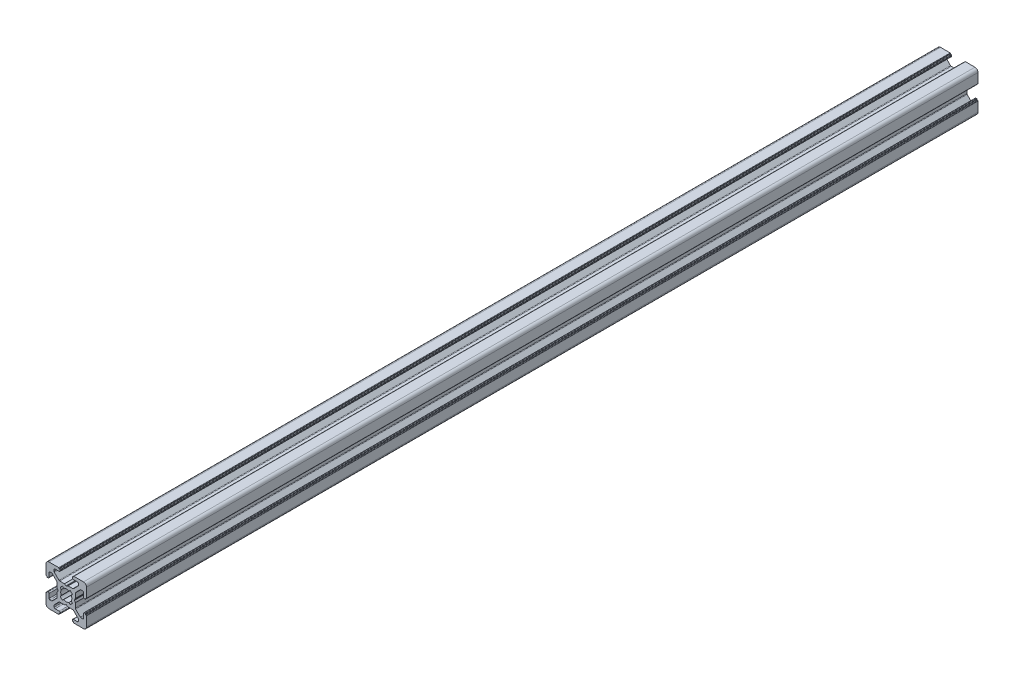
SolidWorks part; units mm, degrees
ref_plane "Ön Düzlem" through (0, 0, 0) normal (0, 0, 1) x (1, 0, 0)
ref_plane "Üst Düzlem" through (0, 0, 0) normal (0, 1, 0) x (1, 0, 0)
ref_plane "Sağ Düzlem" through (0, 0, 0) normal (1, 0, 0) x (0, 0, -1)
sketch "Çizim1" plane through (0, 0, 0) normal (0, 0, 1) x (1, 0, 0)
  line L0 (-2.9922, 1.9099) -> (-2.4453, 1.2582)
  line L1 (-2.4453, -1.2582) -> (-2.9922, -1.9099)
  line L2 (-1.9139, -2.9896) -> (-1.2582, -2.4453)
  line L3 (1.2582, -2.4453) -> (1.9139, -2.9896)
  line L4 (2.9922, -1.9099) -> (2.4453, -1.2582)
  line L5 (2.4453, 1.2582) -> (2.9922, 1.9099)
  line L6 (1.9139, 2.9896) -> (1.2582, 2.4453)
  line L7 (-1.2582, 2.4453) -> (-1.9139, 2.9896)
  line L8 (-3.75, 10) -> (-8.5, 10)
  line L9 (-3.55, 9.7) -> (-3.55, 9.8)
  line L10 (-3.2, 9.5) -> (-3.35, 9.5)
  line L11 (-3, 9) -> (-3, 9.3)
  line L12 (-5.5, 8.5) -> (-3.5, 8.5)
  line L13 (-6, 7.2678) -> (-6, 8)
  line L14 (-3.5858, 4.6464) -> (-5.8536, 6.9142)
  line L15 (-0.9536, 4.5) -> (-3.2322, 4.5)
  line L16 (-0.1, 4.0381) -> (-0.8536, 4.4732)
  line L17 (0.8536, 4.4732) -> (0.1, 4.0381)
  line L18 (3.2322, 4.5) -> (0.9536, 4.5)
  line L19 (5.8536, 6.9142) -> (3.5858, 4.6464)
  line L20 (6, 8) -> (6, 7.2678)
  line L21 (3.5, 8.5) -> (5.5, 8.5)
  line L22 (3, 9.3) -> (3, 9)
  line L23 (3.35, 9.5) -> (3.2, 9.5)
  line L24 (3.55, 9.8) -> (3.55, 9.7)
  line L25 (8.5, 10) -> (3.75, 10)
  line L26 (10, 3.75) -> (10, 8.5)
  line L27 (9.7, 3.55) -> (9.8, 3.55)
  line L28 (9.5, 3.2) -> (9.5, 3.35)
  line L29 (9, 3) -> (9.3, 3)
  line L30 (8.5, 5.5) -> (8.5, 3.5)
  line L31 (7.2678, 6) -> (8, 6)
  line L32 (4.6464, 3.5858) -> (6.9142, 5.8536)
  line L33 (4.5, 0.9536) -> (4.5, 3.2322)
  line L34 (4.0381, 0.1) -> (4.4732, 0.8536)
  line L35 (4.4732, -0.8536) -> (4.0381, -0.1)
  line L36 (4.5, -3.2322) -> (4.5, -0.9536)
  line L37 (6.9142, -5.8536) -> (4.6464, -3.5858)
  line L38 (8, -6) -> (7.2678, -6)
  line L39 (8.5, -3.5) -> (8.5, -5.5)
  line L40 (9.3, -3) -> (9, -3)
  line L41 (9.5, -3.35) -> (9.5, -3.2)
  line L42 (9.8, -3.55) -> (9.7, -3.55)
  line L43 (10, -8.5) -> (10, -3.75)
  line L44 (3.75, -10) -> (8.5, -10)
  line L45 (3.55, -9.7) -> (3.55, -9.8)
  line L46 (3.2, -9.5) -> (3.35, -9.5)
  line L47 (3, -9) -> (3, -9.3)
  line L48 (5.5, -8.5) -> (3.5, -8.5)
  line L49 (6, -7.2678) -> (6, -8)
  line L50 (3.5858, -4.6464) -> (5.8536, -6.9142)
  line L51 (0.9536, -4.5) -> (3.2322, -4.5)
  line L52 (0.1, -4.0381) -> (0.8536, -4.4732)
  line L53 (-0.8536, -4.4732) -> (-0.1, -4.0381)
  line L54 (-3.2322, -4.5) -> (-0.9536, -4.5)
  line L55 (-5.8536, -6.9142) -> (-3.5858, -4.6464)
  line L56 (-6, -8) -> (-6, -7.2678)
  line L57 (-3.5, -8.5) -> (-5.5, -8.5)
  line L58 (-3, -9.3) -> (-3, -9)
  line L59 (-3.35, -9.5) -> (-3.2, -9.5)
  line L60 (-3.55, -9.8) -> (-3.55, -9.7)
  line L61 (-8.5, -10) -> (-3.75, -10)
  line L62 (-10, -3.75) -> (-10, -8.5)
  line L63 (-9.7, -3.55) -> (-9.8, -3.55)
  line L64 (-9.5, -3.2) -> (-9.5, -3.35)
  line L65 (-9, -3) -> (-9.3, -3)
  line L66 (-8.5, -5.5) -> (-8.5, -3.5)
  line L67 (-7.2678, -6) -> (-8, -6)
  line L68 (-4.6464, -3.5858) -> (-6.9142, -5.8536)
  line L69 (-4.5, -0.9536) -> (-4.5, -3.2322)
  line L70 (-4.0381, -0.1) -> (-4.4732, -0.8536)
  line L71 (-4.4732, 0.8536) -> (-4.0381, 0.1)
  line L72 (-4.5, 3.2322) -> (-4.5, 0.9536)
  line L73 (-6.9142, 5.8536) -> (-4.6464, 3.5858)
  line L74 (-8, 6) -> (-7.2678, 6)
  line L75 (-8.5, 3.5) -> (-8.5, 5.5)
  line L76 (-9.3, 3) -> (-9, 3)
  line L77 (-9.5, 3.35) -> (-9.5, 3.2)
  line L78 (-9.8, 3.55) -> (-9.7, 3.55)
  line L79 (-10, 8.5) -> (-10, 3.75)
  arc A0 (-2.4453, 1.2582) -> (-2.4453, -1.2582) centre (0, 0) ccw
  arc A1 (-2.9922, -1.9099) -> (-1.9139, -2.9896) centre (0, 0) ccw
  arc A2 (-1.2582, -2.4453) -> (1.2582, -2.4453) centre (0, 0) ccw
  arc A3 (1.9139, -2.9896) -> (2.9922, -1.9099) centre (0, 0) ccw
  arc A4 (2.4453, -1.2582) -> (2.4453, 1.2582) centre (0, 0) ccw
  arc A5 (2.9922, 1.9099) -> (1.9139, 2.9896) centre (0, 0) ccw
  arc A6 (1.2582, 2.4453) -> (-1.2582, 2.4453) centre (0, 0) ccw
  arc A7 (-1.9139, 2.9896) -> (-2.9922, 1.9099) centre (0, 0) ccw
  arc A8 (-3.55, 9.8) -> (-3.75, 10) centre (-3.75, 9.8) ccw
  arc A9 (-3.55, 9.7) -> (-3.35, 9.5) centre (-3.35, 9.7) ccw
  arc A10 (-3, 9.3) -> (-3.2, 9.5) centre (-3.2, 9.3) ccw
  arc A11 (-3.5, 8.5) -> (-3, 9) centre (-3.5, 9) ccw
  arc A12 (-5.5, 8.5) -> (-6, 8) centre (-5.5, 8) ccw
  arc A13 (-6, 7.2678) -> (-5.8536, 6.9142) centre (-5.5, 7.2678) ccw
  arc A14 (-3.5858, 4.6464) -> (-3.2322, 4.5) centre (-3.2322, 5) ccw
  arc A15 (-0.8536, 4.4732) -> (-0.9536, 4.5) centre (-0.9536, 4.3) ccw
  arc A16 (-0.1, 4.0381) -> (0.1, 4.0381) centre (0, 4.2113) ccw
  arc A17 (0.9536, 4.5) -> (0.8536, 4.4732) centre (0.9536, 4.3) ccw
  arc A18 (3.2322, 4.5) -> (3.5858, 4.6464) centre (3.2322, 5) ccw
  arc A19 (5.8536, 6.9142) -> (6, 7.2678) centre (5.5, 7.2678) ccw
  arc A20 (6, 8) -> (5.5, 8.5) centre (5.5, 8) ccw
  arc A21 (3, 9) -> (3.5, 8.5) centre (3.5, 9) ccw
  arc A22 (3.2, 9.5) -> (3, 9.3) centre (3.2, 9.3) ccw
  arc A23 (3.35, 9.5) -> (3.55, 9.7) centre (3.35, 9.7) ccw
  arc A24 (3.75, 10) -> (3.55, 9.8) centre (3.75, 9.8) ccw
  arc A25 (10, 8.5) -> (8.5, 10) centre (8.5, 8.5) ccw
  arc A26 (9.8, 3.55) -> (10, 3.75) centre (9.8, 3.75) ccw
  arc A27 (9.7, 3.55) -> (9.5, 3.35) centre (9.7, 3.35) ccw
  arc A28 (9.3, 3) -> (9.5, 3.2) centre (9.3, 3.2) ccw
  arc A29 (8.5, 3.5) -> (9, 3) centre (9, 3.5) ccw
  arc A30 (8.5, 5.5) -> (8, 6) centre (8, 5.5) ccw
  arc A31 (7.2678, 6) -> (6.9142, 5.8536) centre (7.2678, 5.5) ccw
  arc A32 (4.6464, 3.5858) -> (4.5, 3.2322) centre (5, 3.2322) ccw
  arc A33 (4.4732, 0.8536) -> (4.5, 0.9536) centre (4.3, 0.9536) ccw
  arc A34 (4.0381, 0.1) -> (4.0381, -0.1) centre (4.2113, 0) ccw
  arc A35 (4.5, -0.9536) -> (4.4732, -0.8536) centre (4.3, -0.9536) ccw
  arc A36 (4.5, -3.2322) -> (4.6464, -3.5858) centre (5, -3.2322) ccw
  arc A37 (6.9142, -5.8536) -> (7.2678, -6) centre (7.2678, -5.5) ccw
  arc A38 (8, -6) -> (8.5, -5.5) centre (8, -5.5) ccw
  arc A39 (9, -3) -> (8.5, -3.5) centre (9, -3.5) ccw
  arc A40 (9.5, -3.2) -> (9.3, -3) centre (9.3, -3.2) ccw
  arc A41 (9.5, -3.35) -> (9.7, -3.55) centre (9.7, -3.35) ccw
  arc A42 (10, -3.75) -> (9.8, -3.55) centre (9.8, -3.75) ccw
  arc A43 (8.5, -10) -> (10, -8.5) centre (8.5, -8.5) ccw
  arc A44 (3.55, -9.8) -> (3.75, -10) centre (3.75, -9.8) ccw
  arc A45 (3.55, -9.7) -> (3.35, -9.5) centre (3.35, -9.7) ccw
  arc A46 (3, -9.3) -> (3.2, -9.5) centre (3.2, -9.3) ccw
  arc A47 (3.5, -8.5) -> (3, -9) centre (3.5, -9) ccw
  arc A48 (5.5, -8.5) -> (6, -8) centre (5.5, -8) ccw
  arc A49 (6, -7.2678) -> (5.8536, -6.9142) centre (5.5, -7.2678) ccw
  arc A50 (3.5858, -4.6464) -> (3.2322, -4.5) centre (3.2322, -5) ccw
  arc A51 (0.8536, -4.4732) -> (0.9536, -4.5) centre (0.9536, -4.3) ccw
  arc A52 (0.1, -4.0381) -> (-0.1, -4.0381) centre (0, -4.2113) ccw
  arc A53 (-0.9536, -4.5) -> (-0.8536, -4.4732) centre (-0.9536, -4.3) ccw
  arc A54 (-3.2322, -4.5) -> (-3.5858, -4.6464) centre (-3.2322, -5) ccw
  arc A55 (-5.8536, -6.9142) -> (-6, -7.2678) centre (-5.5, -7.2678) ccw
  arc A56 (-6, -8) -> (-5.5, -8.5) centre (-5.5, -8) ccw
  arc A57 (-3, -9) -> (-3.5, -8.5) centre (-3.5, -9) ccw
  arc A58 (-3.2, -9.5) -> (-3, -9.3) centre (-3.2, -9.3) ccw
  arc A59 (-3.35, -9.5) -> (-3.55, -9.7) centre (-3.35, -9.7) ccw
  arc A60 (-3.75, -10) -> (-3.55, -9.8) centre (-3.75, -9.8) ccw
  arc A61 (-10, -8.5) -> (-8.5, -10) centre (-8.5, -8.5) ccw
  arc A62 (-9.8, -3.55) -> (-10, -3.75) centre (-9.8, -3.75) ccw
  arc A63 (-9.7, -3.55) -> (-9.5, -3.35) centre (-9.7, -3.35) ccw
  arc A64 (-9.3, -3) -> (-9.5, -3.2) centre (-9.3, -3.2) ccw
  arc A65 (-8.5, -3.5) -> (-9, -3) centre (-9, -3.5) ccw
  arc A66 (-8.5, -5.5) -> (-8, -6) centre (-8, -5.5) ccw
  arc A67 (-7.2678, -6) -> (-6.9142, -5.8536) centre (-7.2678, -5.5) ccw
  arc A68 (-4.6464, -3.5858) -> (-4.5, -3.2322) centre (-5, -3.2322) ccw
  arc A69 (-4.4732, -0.8536) -> (-4.5, -0.9536) centre (-4.3, -0.9536) ccw
  arc A70 (-4.0381, -0.1) -> (-4.0381, 0.1) centre (-4.2113, 0) ccw
  arc A71 (-4.5, 0.9536) -> (-4.4732, 0.8536) centre (-4.3, 0.9536) ccw
  arc A72 (-4.5, 3.2322) -> (-4.6464, 3.5858) centre (-5, 3.2322) ccw
  arc A73 (-6.9142, 5.8536) -> (-7.2678, 6) centre (-7.2678, 5.5) ccw
  arc A74 (-8, 6) -> (-8.5, 5.5) centre (-8, 5.5) ccw
  arc A75 (-9, 3) -> (-8.5, 3.5) centre (-9, 3.5) ccw
  arc A76 (-9.5, 3.2) -> (-9.3, 3) centre (-9.3, 3.2) ccw
  arc A77 (-9.5, 3.35) -> (-9.7, 3.55) centre (-9.7, 3.35) ccw
  arc A78 (-10, 3.75) -> (-9.8, 3.55) centre (-9.8, 3.75) ccw
  arc A79 (-8.5, 10) -> (-10, 8.5) centre (-8.5, 8.5) ccw
extrude "Yükseklik-Ekstrüzyon1" add sketch "Çizim1" along normal mid plane 440
